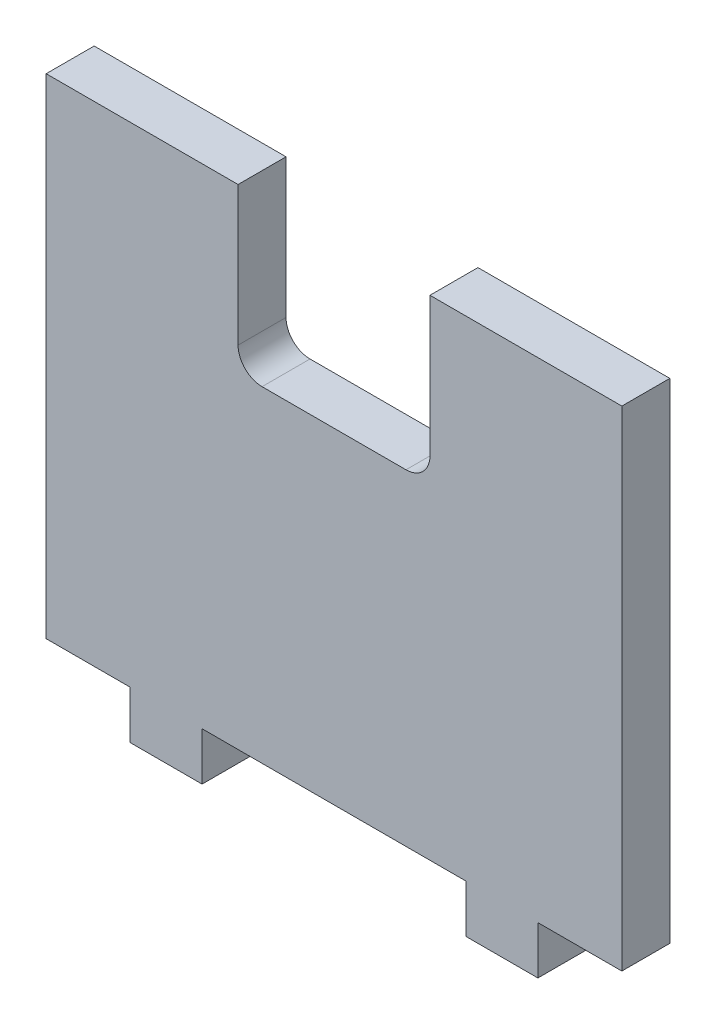
SolidWorks part; units mm, degrees
material "Acrylic (Medium-high impact)"
ref_plane "Front Plane" through (0, 0, 0) normal (0, 0, 1) x (1, 0, 0)
ref_plane "Top Plane" through (0, 0, 0) normal (0, 1, 0) x (1, 0, 0)
ref_plane "Right Plane" through (0, 0, 0) normal (1, 0, 0) x (0, 0, -1)
sketch "Sketch1" plane through (0, 0, 0) normal (0, 0, 1) x (1, 0, 0)
  line L0 (53.975, 0) -> (34.925, 0) construction
  line L1 (-76.2, 142.24) -> (76.2, 142.24)
  line L2 (-76.2, 142.24) -> (-76.2, 12.7)
  line L3 (-76.2, 12.7) -> (-53.975, 12.7)
  line L4 (76.2, 142.24) -> (76.2, 12.7)
  line L5 (53.975, 0) -> (53.975, 12.7) construction
  line L6 (34.925, 0) -> (34.925, 12.7) construction
  line L7 (-34.925, 0) -> (-53.975, 0) construction
  line L8 (-34.925, 0) -> (-34.925, 12.7) construction
  line L9 (-53.975, 0) -> (-53.975, 12.7) construction
  line L10 (53.975, 0) -> (34.925, 0)
  line L11 (53.975, 0) -> (53.975, 12.7)
  line L12 (34.925, 0) -> (34.925, 12.7)
  line L13 (-34.925, 0) -> (-53.975, 0)
  line L14 (-34.925, 0) -> (-34.925, 12.7)
  line L15 (-53.975, 0) -> (-53.975, 12.7)
  line L16 (-34.925, 12.7) -> (34.925, 12.7)
  line L17 (53.975, 12.7) -> (76.2, 12.7)
extrude "Extrude1" add sketch "Sketch1" against normal blind 12.7
sketch "Sketch2" plane through (0, 0, 0) normal (0, 0, 1) x (1, 0, 0)
  line L0 (76.2, 142.24) -> (-76.2, 142.24) construction
  line L1 (-25.4, 142.24) -> (25.4, 142.24)
  line L2 (-25.4, 142.24) -> (-25.4, 99.06)
  line L3 (-25.4, 99.06) -> (25.4, 99.06)
  line L4 (25.4, 142.24) -> (25.4, 99.06)
  point P6 (0, 99.06)
  dimension "D1" = 43.18
  dimension "D2" = 50.8
extrude "Cut-Extrude1" cut sketch "Sketch2" against normal through all
fillet "Fillet1" radius 6.35 2 edges at (25.4, 99.06, -6.35) (-25.4, 99.06, -6.35)
